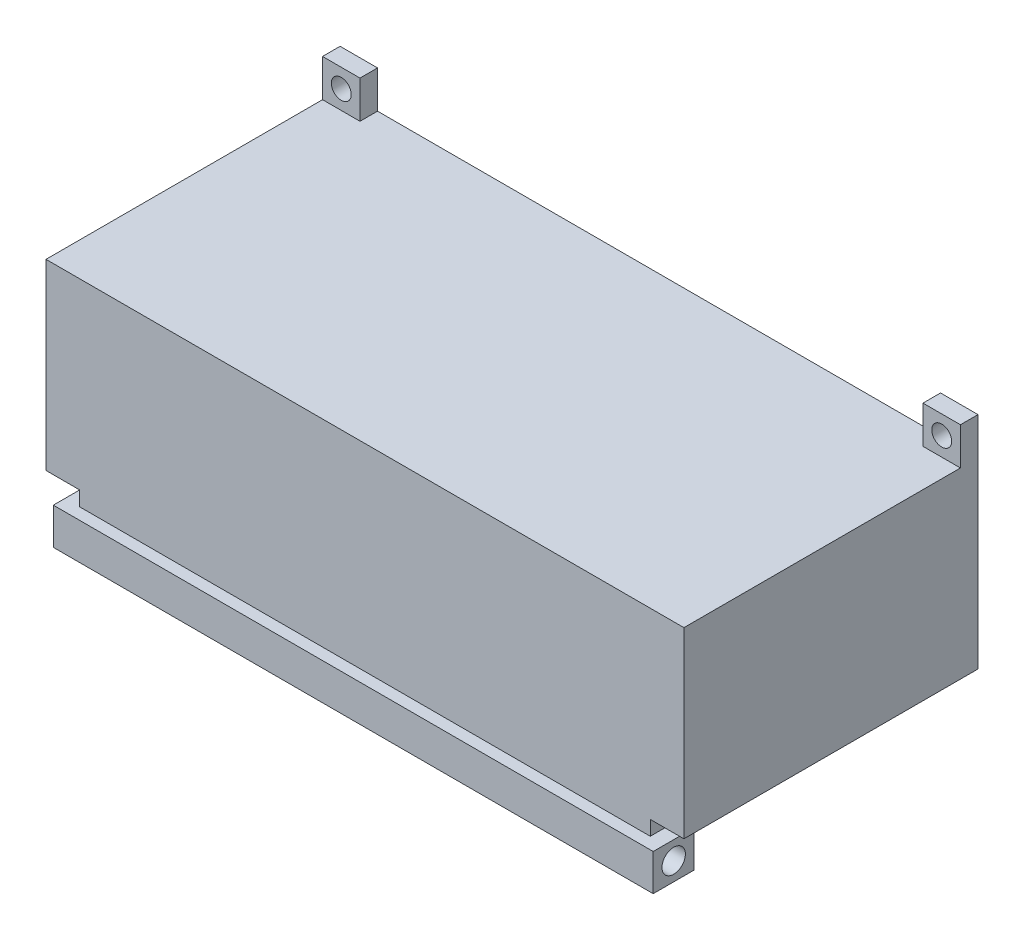
SolidWorks part; units mm, degrees
ref_plane "Front Plane" through (0, 0, 0) normal (0, 0, 1) x (1, 0, 0)
ref_plane "Top Plane" through (0, 0, 0) normal (0, 1, 0) x (1, 0, 0)
ref_plane "Right Plane" through (0, 0, 0) normal (1, 0, 0) x (0, 0, -1)
sketch "Sketch4" plane through (0, 0, 0) normal (0, 0, 1) x (1, 0, 0)
  line L1 (3.25, 0) -> (105.75, 0)
  line L2 (0, 8.75) -> (0, 40)
  line L3 (0, 40) -> (109, 40)
  line L4 (109, 8.75) -> (109, 40)
  line L5 (3.25, 6.25) -> (5.75, 6.25)
  line L7 (0, 8.75) -> (5.75, 8.75)
  line L8 (5.75, 6.25) -> (5.75, 8.75)
  line L9 (105.75, 6.25) -> (103.25, 6.25)
  line L11 (109, 8.75) -> (103.25, 8.75)
  line L12 (103.25, 6.25) -> (103.25, 8.75)
  line L16 (3.25, 0) -> (3.25, 6.25)
  line L20 (105.75, 0) -> (105.75, 6.25)
  point P0 (105.602, 0.15)
  dimension "D1" = 40
  dimension "D2" = 109
  dimension "D3" = 6.25
  dimension "D4" = 2.5
  dimension "D5" = 2.5
  dimension "D6" = 3.25
  dimension "D7" = 2.5
  dimension "D8" = 3.25
extrude "Boss-Extrude2" add sketch "Sketch4" along normal blind 50.25
sketch "Sketch5" plane through (0, 0, 0) normal (0, -1, 0) x (1, 0, 0)
  line L0 (3.25, 0) -> (105.75, 0) construction
  line L1 (8.4186, 0) -> (100.8159, 0)
  line L2 (8.25, 45.25) -> (8.25, 47.25)
  line L3 (8.25, 47.25) -> (100.75, 47.25)
  line L4 (100.75, 45.25) -> (100.75, 47.25)
  line L5 (3.25, 50.25) -> (105.75, 50.25) construction
  line L6 (105.75, 50.25) -> (105.75, 0) construction
  line L7 (3.25, 0) -> (105.75, 0)
  line L8 (3.25, 0) -> (3.25, 45.25)
  line L9 (3.25, 45.25) -> (8.25, 45.25)
  line L10 (105.75, 0) -> (105.75, 45.25)
  line L11 (100.75, 45.25) -> (105.75, 45.25)
  line M10 (3.25, 0) -> (105.75, 0)
  line M11 (105.75, 0) -> (105.75, 50.25)
  line M13 (3.25, 50.25) -> (3.25, 0)
  dimension "D1" = 3
  dimension "D2" = 2
  dimension "D3" = 5
  dimension "D4" = 5
extrude "Cut-Extrude3" cut sketch "Sketch5" against normal offset from surface (37 mm away) 3 contours L11 L4 L3 L2 L9 M13 M10 M11 up to face at (54.5, 40, 25.125)
sketch "Sketch6" plane through (0, 0, 0) normal (0, 0, -1) x (-1, 0, 0)
  line L0 (-109, 40) -> (-109, 46.4)
  line L1 (-109, 46.4) -> (-102.6, 46.4)
  line L2 (-102.6, 46.4) -> (-102.6, 40)
  line L3 (-109, 40) -> (0, 40) construction
  line L4 (-54.5, 40) -> (-54.5, 46.516) construction
  line L5 (-6.4, 46.4) -> (-6.4, 40)
  line L6 (0, 46.4) -> (-6.4, 46.4)
  line L7 (0, 40) -> (0, 46.4)
  circle A0 centre (-105.8, 43.2) radius 1.7
  circle A1 centre (-3.2, 43.2) radius 1.7
  point P11 (-105.5843, 41.359)
  point P12 (-102.6, 43.2)
  point P13 (-105.8, 46.4)
  line M10 (0, 40) -> (-109, 40)
  dimension "D1" = 3.4
  dimension "D2" = 3.2
  dimension "D3" = 3.2
extrude "Boss-Extrude3" add sketch "Sketch6" against normal blind 3 contours L2 L1 L0 A0 M10 | L7 L6 L5 A1 M10
sketch "Sketch8" plane through (0, 0, 50.25) normal (0, 0, 1) x (1, 0, 0)
  line L1 (3.25, 0) -> (105.75, 0)
  line L2 (3.25, 0) -> (3.25, 6.25)
  line L3 (3.25, 6.25) -> (105.75, 6.25)
  line L4 (105.75, 0) -> (105.75, 6.25)
extrude "Boss-Extrude4" add sketch "Sketch8" along normal blind 2
sketch "Sketch7" plane through (105.75, 0, 0) normal (1, 0, 0) x (0, 0, -1)
  line L0 (-45.25, 6.25) -> (-45.25, 0) construction
  line L1 (-52.25, 0) -> (-45.25, 0) construction
  circle A0 centre (-48.75, 3.125) radius 2
  point P2 (-48.7406, 3.0981)
  point P3 (0, 0)
  point P6 (-45.25, 3.125)
  point P9 (-48.75, 0)
  dimension "D1" = 4
extrude "Cut-Extrude4" cut sketch "Sketch7" against normal blind 7
ref_plane "Plane1" through (54.5, 0, 0) normal (1, 0, 0) x (0, 0, -1)
mirror "Mirror1" about plane through (54.5, 0, 0) normal (1, 0, 0) of "Cut-Extrude4"
